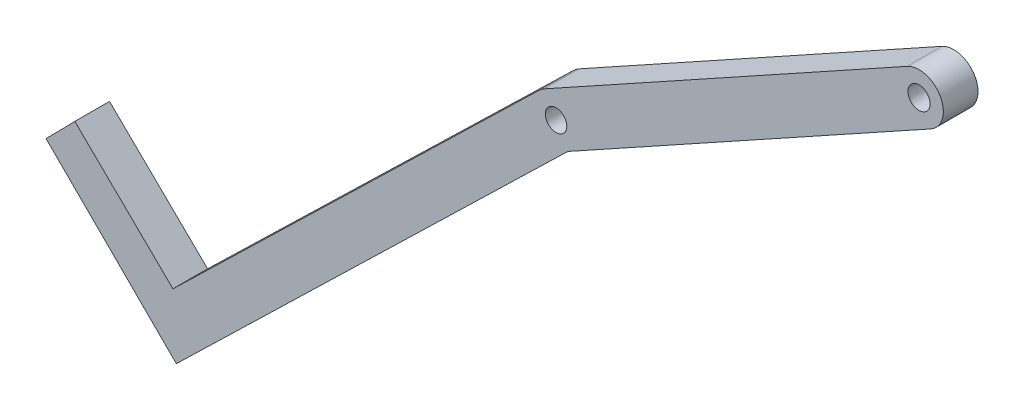
SolidWorks part; units mm, degrees
material "PLA"
ref_plane "Front Plane" through (0, 0, 0) normal (0, 0, 1) x (1, 0, 0)
ref_plane "Top Plane" through (0, 0, 0) normal (0, 1, 0) x (1, 0, 0)
ref_plane "Right Plane" through (0, 0, 0) normal (1, 0, 0) x (0, 0, -1)
sketch "Sketch1" plane through (0, 0, 0) normal (0, 0, 1) x (1, 0, 0)
  line L0 (-52.0749, -28.9974) -> (0.2795, -0.0072) construction
  line L1 (-53.7704, -25.9355) -> (-1.416, 3.0547)
  line L2 (-50.3794, -32.0593) -> (1.975, -3.0691)
  line L3 (-52.0749, -28.9974) -> (-107.222, -82.4619) construction
  line L4 (-107.222, -82.4619) -> (-123.8104, -66.2402) construction
  line L6 (-123.8104, -66.2402) -> (-121.4739, -63.8509)
  line L7 (-121.4739, -63.8509) -> (-107.325, -77.687)
  line L8 (-107.325, -77.687) -> (-54.5111, -26.4845)
  line L9 (-123.8104, -66.2402) -> (-125.6315, -68.0683)
  line L10 (-125.6315, -68.0683) -> (-106.8354, -86.7928)
  line L11 (-106.8354, -86.7928) -> (-50.3794, -32.0593)
  circle A0 centre (-52.0749, -28.9974) radius 1.55 construction
  circle A1 centre (0.2795, -0.0072) radius 1.6
  circle A6 centre (0.2795, -0.0072) radius 1.6 construction
  circle A7 centre (-52.0749, -28.9974) radius 1.55
  circle A8 centre (0.2795, -0.0072) radius 3.5
  circle A9 centre (-52.0749, -28.9974) radius 3.5
  point P3 (0, 0)
  dimension "D1" = 7
  dimension "D2" = 7
  dimension "D3" = 78.6322
  dimension "D4" = 73.5595
extrude "Boss-Extrude1" add sketch "Sketch1" along normal blind 5 contours A9 L8 L7 L6 L9 L10 L11 | A9 L2 A8 L1 | A9 A7 | A8 A1
